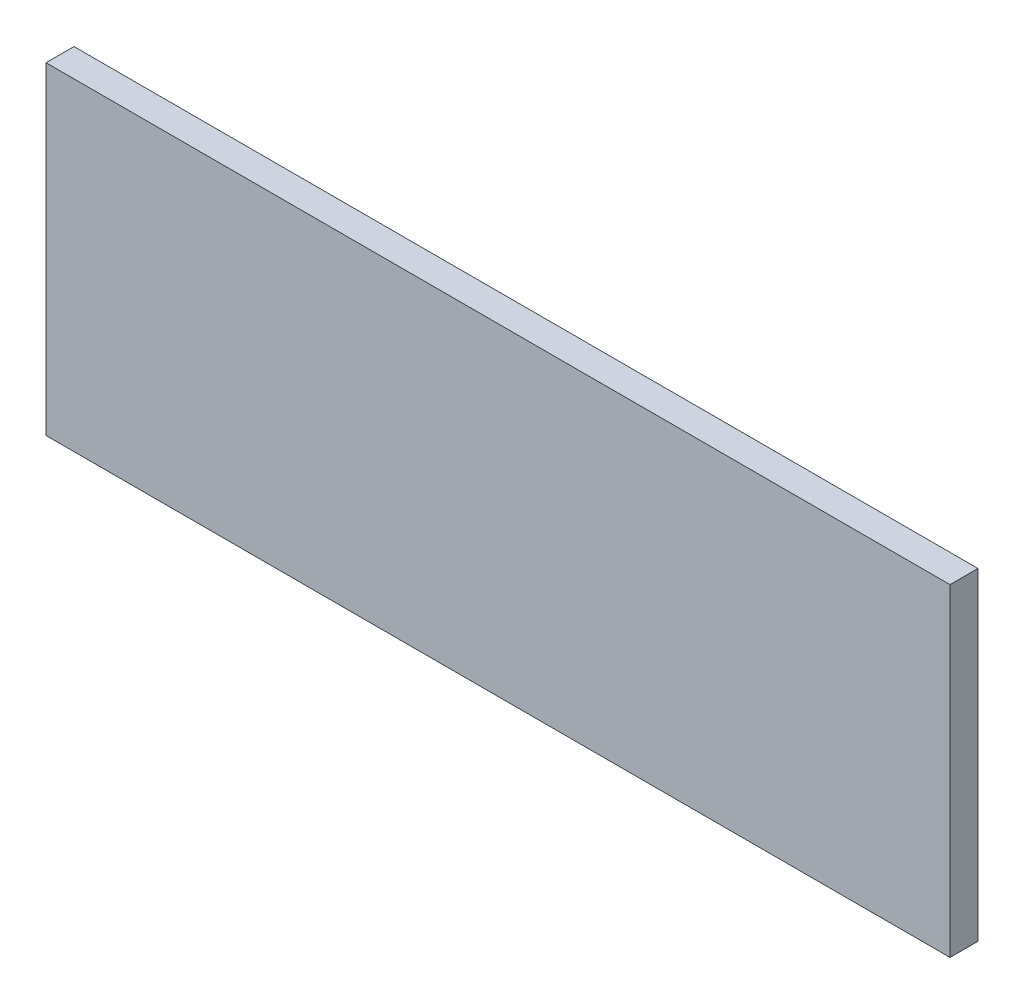
SolidWorks part; units mm, degrees
ref_plane "正面" through (0, 0, 0) normal (0, 0, 1) x (1, 0, 0)
ref_plane "平面" through (0, 0, 0) normal (0, 1, 0) x (1, 0, 0)
ref_plane "右側面" through (0, 0, 0) normal (1, 0, 0) x (0, 0, -1)
sketch "ｽｹｯﾁ1" plane through (0, 0, 0) normal (0, 0, 1) x (1, 0, 0)
  line L1 (-69.2801, 161.5071) -> (350.7199, 161.5071)
  line L2 (-69.2801, 161.5071) -> (-69.2801, 11.5071)
  line L3 (-69.2801, 11.5071) -> (350.7199, 11.5071)
  line L4 (350.7199, 161.5071) -> (350.7199, 11.5071)
  dimension "D1" = 420
  dimension "D3" = 150
extrude "ﾎﾞｽ - 押し出し1" add sketch "ｽｹｯﾁ1" along normal blind 13
